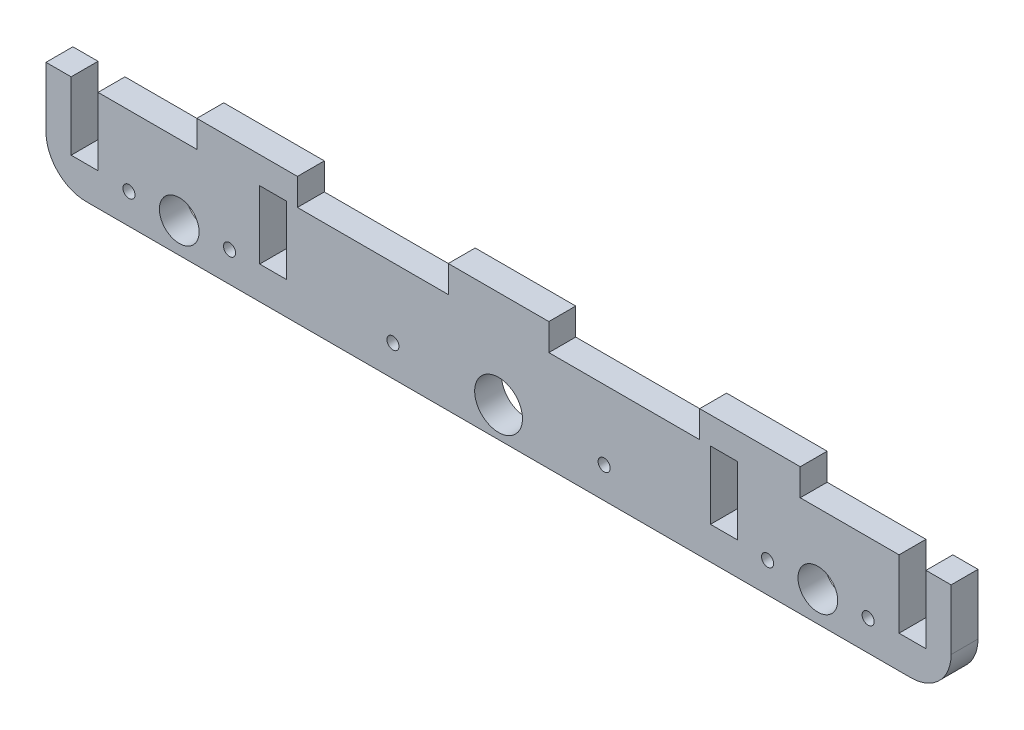
SolidWorks part; units mm, degrees
ref_plane "Front Plane" through (0, 0, 0) normal (0, 0, 1) x (1, 0, 0)
ref_plane "Top Plane" through (0, 0, 0) normal (0, 1, 0) x (1, 0, 0)
ref_plane "Right Plane" through (0, 0, 0) normal (1, 0, 0) x (0, 0, -1)
sketch "Model" plane through (0, 0, 0) normal (0, 0, 1) x (1, 0, 0)
  line L0 (-40, 20) -> (-10, 20)
  line L1 (-82, 0) -> (82, 0)
  line L2 (-90, 8) -> (-90, 20)
  line L3 (-90, 20) -> (-85, 20)
  line L4 (90, 8) -> (90, 20)
  line L5 (10, 20) -> (40, 20)
  line L6 (-60, 20) -> (-60, 25.35)
  line L7 (-60, 25.35) -> (-40, 25.35)
  line L8 (-40, 20) -> (-40, 25.35)
  line L9 (85, 20) -> (90, 20)
  line L10 (60, 20) -> (60, 25.35)
  line L11 (60, 25.35) -> (40, 25.35)
  line L12 (40, 20) -> (40, 25.35)
  line L13 (60, 20) -> (79.65, 20)
  line L14 (10, 20) -> (10, 25.35)
  line L15 (10, 25.35) -> (-10, 25.35)
  line L16 (-10, 20) -> (-10, 25.35)
  line L17 (0, 0) -> (0, 25.35) construction
  line L18 (-85, 20) -> (-85, 6.5)
  line L19 (-85, 6.5) -> (-79.65, 6.5)
  line L20 (-79.65, 20) -> (-79.65, 6.5)
  line L21 (-79.65, 20) -> (-60, 20)
  line L22 (79.65, 20) -> (79.65, 6.5)
  line L23 (79.65, 6.5) -> (85, 6.5)
  line L24 (85, 20) -> (85, 6.5)
  line L25 (90, 6) -> (-90, 6) construction
  line L26 (-47.5, 20) -> (-42.15, 20)
  line L27 (-47.5, 20) -> (-47.5, 6.5)
  line L28 (-47.5, 6.5) -> (-42.15, 6.5)
  line L29 (-42.15, 20) -> (-42.15, 6.5)
  line L30 (47.5, 20) -> (42.15, 20)
  line L31 (42.15, 20) -> (42.15, 6.5)
  line L32 (47.5, 6.5) -> (42.15, 6.5)
  line L33 (47.5, 20) -> (47.5, 6.5)
  arc A0 (82, 0) -> (90, 8) centre (82, 8) ccw
  arc A1 (-90, 8) -> (-82, 0) centre (-82, 8) ccw
  circle A2 centre (0, 6) radius 4.75
  circle A3 centre (-63.5, 6) radius 3.95
  circle A4 centre (-53.5, 6) radius 1.2
  circle A5 centre (-73.5, 6) radius 1.2
  circle A6 centre (-21, 6.16) radius 1.2
  circle A7 centre (73.5, 6) radius 1.2
  circle A8 centre (63.5, 6) radius 3.95
  circle A9 centre (53.5, 6) radius 1.2
  circle A10 centre (21, 6.16) radius 1.2
  dimension "D1" = 8
  dimension "D39" = 9.5
  dimension "D42" = 7.9
  dimension "D43" = 2.4
  dimension "D6" = 20
  dimension "D8" = 5.35
  dimension "D10" = 13.5
  dimension "D15" = 5
  dimension "D16" = 20
  dimension "D18" = 180
  dimension "D22" = 30
  dimension "D24" = 5.35
  dimension "D33" = 5.35
  dimension "D34" = 6.5
  dimension "D35" = 13.5
  dimension "D37" = 2.15
  dimension "D38" = 6
  dimension "D49" = 10
  dimension "D50" = 10
  dimension "D52" = 63.5
  dimension "D54" = 21
  dimension "D55" = 6.16
extrude "Boss-Extrude1" add sketch "Model" along normal blind 5.35
equation "\"mdfthick\"=5.35"
equation "\"D8@Model\"=\"mdfthick\""
equation "\"D24@Model\"=\"mdfthick\""
equation "\"D33@Model\"=\"mdfthick\""
equation "\"D1@Boss-Extrude1\"=\"mdfthick\""
